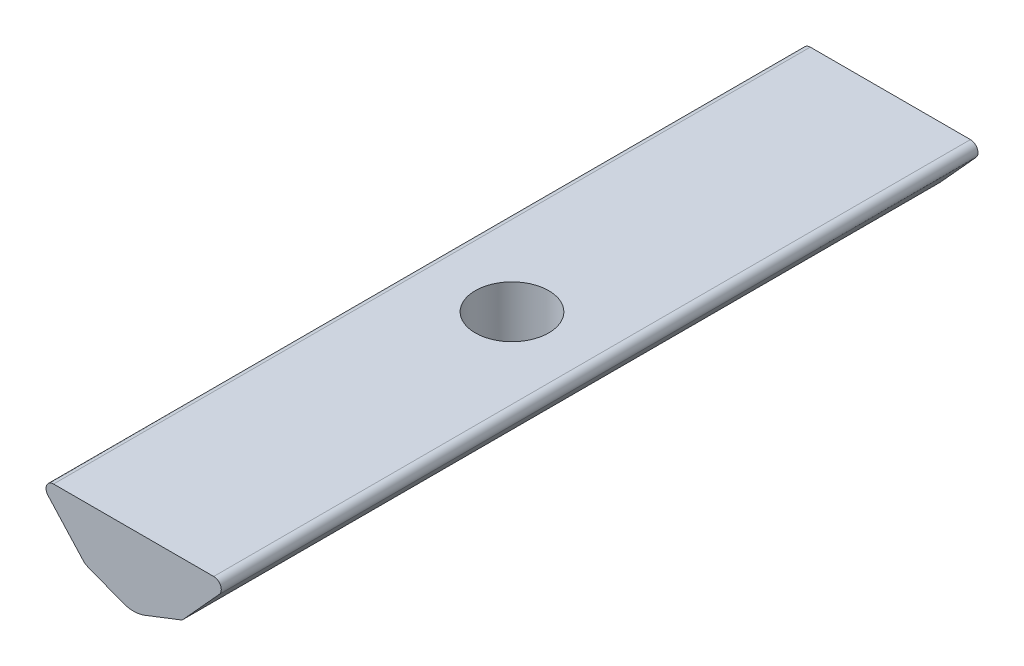
SolidWorks part; units mm, degrees
ref_plane "Front Plane" through (0, 0, 0) normal (0, 0, 1) x (1, 0, 0)
ref_plane "Top Plane" through (0, 0, 0) normal (0, 1, 0) x (1, 0, 0)
ref_plane "Right Plane" through (0, 0, 0) normal (1, 0, 0) x (0, 0, -1)
sketch "Sketch1" plane through (0, 0, 0) normal (0, 0, 1) x (1, 0, 0)
  line L0 (12.5, 4.32) -> (12.5, 10.5371)
  line L1 (10.5371, 12.5) -> (4.32, 12.5)
  line L2 (4.32, 10.36) -> (6.42, 10.36)
  line L3 (7.1337, 8.6353) -> (3.7953, 5.3018)
  line L4 (1.5554, 4.375) -> (-1.5554, 4.375)
  line L5 (-3.7953, 5.3018) -> (-7.1337, 8.6353)
  line L6 (-6.42, 10.36) -> (-4.32, 10.36)
  line L7 (-4.32, 12.5) -> (-10.5371, 12.5)
  line L8 (-12.5, 10.5371) -> (-12.5, 4.32)
  line L9 (-10.36, 4.32) -> (-10.36, 6.3969)
  line L10 (-8.6363, 7.1116) -> (-5.4322, 3.9121)
  line L11 (-4.455, 1.5554) -> (-4.455, -1.5554)
  line L12 (-5.4322, -3.9121) -> (-8.6363, -7.1116)
  line L13 (-10.36, -6.3969) -> (-10.36, -4.32)
  line L14 (-12.5, -4.32) -> (-12.5, -10.5371)
  line L15 (-10.5371, -12.5) -> (-4.3879, -12.5)
  line L16 (-4.3879, -10.36) -> (-6.42, -10.36)
  line L17 (-7.1337, -8.6353) -> (-3.7953, -5.3018)
  line L18 (-1.5554, -4.375) -> (1.5554, -4.375)
  line L19 (3.7953, -5.3018) -> (7.1337, -8.6353)
  line L20 (6.42, -10.36) -> (4.3879, -10.36)
  line L21 (4.3879, -12.5) -> (10.5371, -12.5)
  line L22 (12.5, -10.5371) -> (12.5, -4.32)
  line L23 (10.36, -4.32) -> (10.36, -6.3969)
  line L24 (8.6363, -7.1116) -> (5.4322, -3.9121)
  line L25 (4.455, -1.5554) -> (4.455, 1.5554)
  line L26 (5.4322, 3.9121) -> (8.6363, 7.1116)
  line L27 (10.36, 6.3969) -> (10.36, 4.32)
  circle A0 centre (0, 0) radius 2.5
  arc A1 (12.5, 10.5371) -> (10.5371, 12.5) centre (10.5371, 10.5371) ccw
  arc A2 (4.32, 12.5) -> (4.32, 10.36) centre (4.32, 11.43) ccw
  arc A3 (6.42, 10.36) -> (7.1337, 8.6353) centre (6.42, 9.35) cw
  arc A4 (3.7953, 5.3018) -> (1.5554, 4.375) centre (1.5554, 7.545) cw
  arc A5 (-1.5554, 4.375) -> (-3.7953, 5.3018) centre (-1.5554, 7.545) cw
  arc A6 (-7.1337, 8.6353) -> (-6.42, 10.36) centre (-6.42, 9.35) cw
  arc A7 (-4.32, 10.36) -> (-4.32, 12.5) centre (-4.32, 11.43) ccw
  arc A8 (-10.5371, 12.5) -> (-12.5, 10.5371) centre (-10.5371, 10.5371) ccw
  arc A9 (-12.5, 4.32) -> (-10.36, 4.32) centre (-11.43, 4.32) ccw
  arc A10 (-10.36, 6.3969) -> (-8.6363, 7.1116) centre (-9.35, 6.3969) cw
  arc A11 (-5.4322, 3.9121) -> (-4.455, 1.5554) centre (-7.7855, 1.5554) cw
  arc A12 (-4.455, -1.5554) -> (-5.4322, -3.9121) centre (-7.7855, -1.5554) cw
  arc A13 (-8.6363, -7.1116) -> (-10.36, -6.3969) centre (-9.35, -6.3969) cw
  arc A14 (-10.36, -4.32) -> (-12.5, -4.32) centre (-11.43, -4.32) ccw
  arc A15 (-12.5, -10.5371) -> (-10.5371, -12.5) centre (-10.5371, -10.5371) ccw
  arc A16 (-4.3879, -12.5) -> (-4.3879, -10.36) centre (-4.3879, -11.43) ccw
  arc A17 (-6.42, -10.36) -> (-7.1337, -8.6353) centre (-6.42, -9.35) cw
  arc A18 (-3.7953, -5.3018) -> (-1.5554, -4.375) centre (-1.5554, -7.545) cw
  arc A19 (1.5554, -4.375) -> (3.7953, -5.3018) centre (1.5554, -7.545) cw
  arc A20 (7.1337, -8.6353) -> (6.42, -10.36) centre (6.42, -9.35) cw
  arc A21 (4.3879, -10.36) -> (4.3879, -12.5) centre (4.3879, -11.43) ccw
  arc A22 (10.5371, -12.5) -> (12.5, -10.5371) centre (10.5371, -10.5371) ccw
  arc A23 (12.5, -4.32) -> (10.36, -4.32) centre (11.43, -4.32) ccw
  arc A24 (10.36, -6.3969) -> (8.6363, -7.1116) centre (9.35, -6.3969) cw
  arc A25 (5.4322, -3.9121) -> (4.455, -1.5554) centre (7.7855, -1.5554) cw
  arc A26 (4.455, 1.5554) -> (5.4322, 3.9121) centre (7.7855, 1.5554) cw
  arc A27 (8.6363, 7.1116) -> (10.36, 6.3969) centre (9.35, 6.3969) cw
  arc A28 (10.36, 4.32) -> (12.5, 4.32) centre (11.43, 4.32) ccw
sketch "Sketch2" plane through (0, 0, 0) normal (0, 0, 1) x (1, 0, 0)
  line L0 (0, 0) -> (0, -3.6308) construction
  line L1 (-5.2909, 9.35) -> (5.2909, 9.35)
  line L3 (-0.7249, 4.8469) -> (-3.1002, 5.7707)
  line L4 (-3.2892, 5.9006) -> (-5.6612, 8.514)
  line L5 (3.2892, 5.9006) -> (5.6612, 8.514)
  line L6 (0.7249, 4.8469) -> (3.1002, 5.7707)
  arc A0 (-3.1002, 5.7707) -> (-3.2892, 5.9006) centre (-2.919, 6.2367) cw
  arc A1 (-5.2909, 9.35) -> (-5.6612, 8.514) centre (-5.2909, 8.85) ccw
  arc A2 (5.2909, 9.35) -> (5.6612, 8.514) centre (5.2909, 8.85) cw
  arc A3 (3.1002, 5.7707) -> (3.2892, 5.9006) centre (2.919, 6.2367) ccw
  arc A4 (0.7249, 4.8469) -> (-0.7249, 4.8469) centre (0, 6.7109) cw
  point P13 (-6.42, 9.35)
  point P20 (0, 9.35)
  point P22 (0, 4.565)
  dimension "D1" = 0.5
  dimension "D2" = 2
extrude "Boss-Extrude1" add sketch "Sketch2" along normal blind 50
sketch "Sketch3" plane through (0, 9.35, 0) normal (0, 1, 0) x (1, 0, 0)
  line L0 (0, 0) -> (0, -50) construction
  line L1 (5.2909, -50) -> (-5.2909, -50) construction
  circle A0 centre (0, -25) radius 2.425
  dimension "D1" = 4.85
extrude "Cut-Extrude1" cut sketch "Sketch3" against normal through all
move or copy body "Body-Move/Copy1" [suppressed] bodies to move or copy 102
